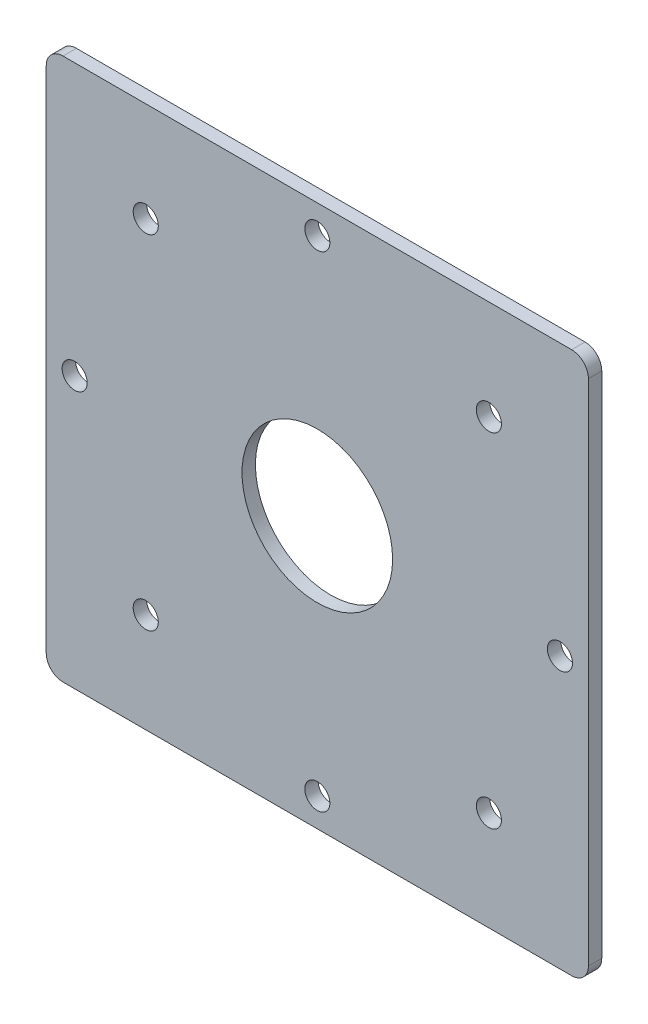
SolidWorks part; units mm, degrees
material "Plain Carbon Steel"
ref_plane "Front Plane" through (0, 0, 0) normal (0, 0, 1) x (1, 0, 0)
ref_plane "Top Plane" through (0, 0, 0) normal (0, 1, 0) x (1, 0, 0)
ref_plane "Right Plane" through (0, 0, 0) normal (1, 0, 0) x (0, 0, -1)
sketch "Sketch1" plane through (0, 0, 0) normal (0, 0, 1) x (1, 0, 0)
  line L1 (-162, -162) -> (162, -162)
  line L2 (-162, -162) -> (-162, 162)
  line L3 (-162, 162) -> (162, 162)
  line L4 (162, -162) -> (162, 162)
  line L5 (-162, -162) -> (162, 162) construction
  line L6 (-162, 162) -> (162, -162) construction
  point P0 (0, 0)
  dimension "D1" = 324
extrude "Boss-Extrude1" add sketch "Sketch1" along normal blind 8
sketch "Sketch2" plane through (0, 0, 8) normal (0, 0, 1) x (1, 0, 0)
  circle A0 centre (0, 0) radius 145 construction
  circle A1 centre (0, 145) radius 7.5
  dimension "D1" = 290
  dimension "D2" = 15
extrude "Cut-Extrude1" cut sketch "Sketch2" against normal blind 8
sketch "Sketch3" plane through (0, 0, 8) normal (0, 0, 1) x (1, 0, 0)
  circle A0 centre (0, 0) radius 45
  dimension "D1" = 90
extrude "Cut-Extrude2" cut sketch "Sketch3" against normal blind 10
pattern_circular "CirPattern1" count 8 over 360 about axis through (0, 0, 0) along (0, 0, 1) of "Cut-Extrude1"
fillet "Fillet1" radius 10 4 edges at (162, -162, 4) (162, 162, 4) (-162, 162, 4) (-162, -162, 4)
